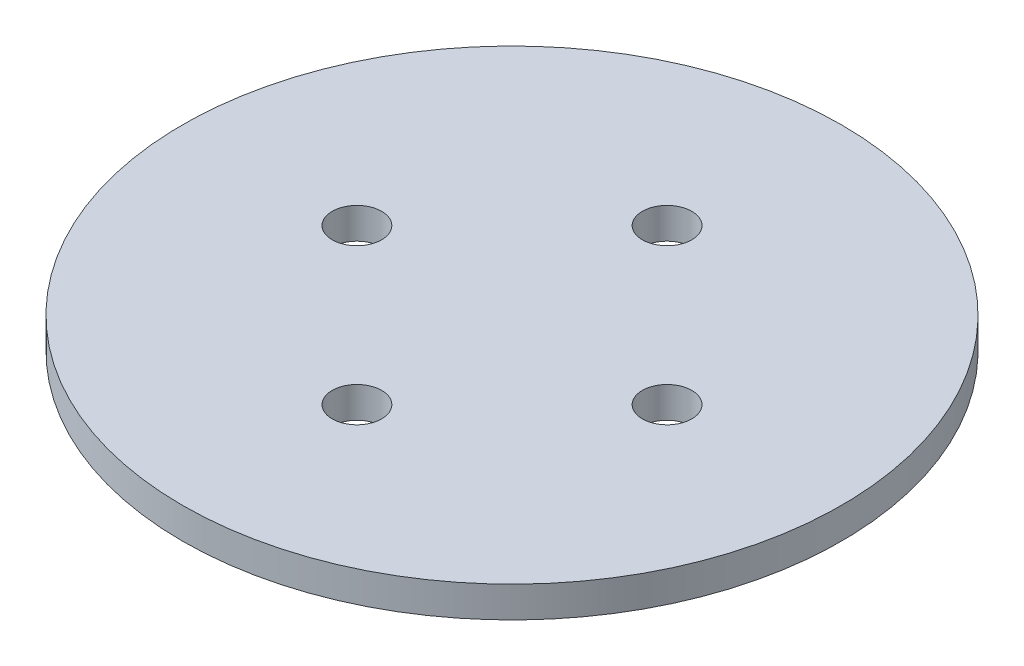
SolidWorks part; units mm, degrees
ref_plane "前视基准面" through (0, 0, 0) normal (0, 0, 1) x (1, 0, 0)
ref_plane "上视基准面" through (0, 0, 0) normal (0, 1, 0) x (1, 0, 0)
ref_plane "右视基准面" through (0, 0, 0) normal (1, 0, 0) x (0, 0, -1)
sketch "草图1" plane through (0, 0, 0) normal (0, 1, 0) x (1, 0, 0)
  circle A0 centre (0, 0) radius 17
  dimension "D1" = 34
extrude "凸台-拉伸1" add sketch "草图1" along normal blind 1.6 contours A0
sketch "草图2" plane through (0, 1.6, 0) normal (0, 1, 0) x (1, 0, 0)
  circle A0 centre (8, 0) radius 1.275
  circle A1 centre (0, -8) radius 1.275
  circle A2 centre (-8, 0) radius 1.275
  circle A3 centre (0, 8) radius 1.275
  point P2 (-9.5984, -1.0231)
  point P4 (0, 0)
  point P12 (0, 0)
  dimension "D1" = 2.55
  dimension "D2" = 8
  dimension "D3" = 4
extrude "切除-拉伸1" cut sketch "草图2" against normal through all
